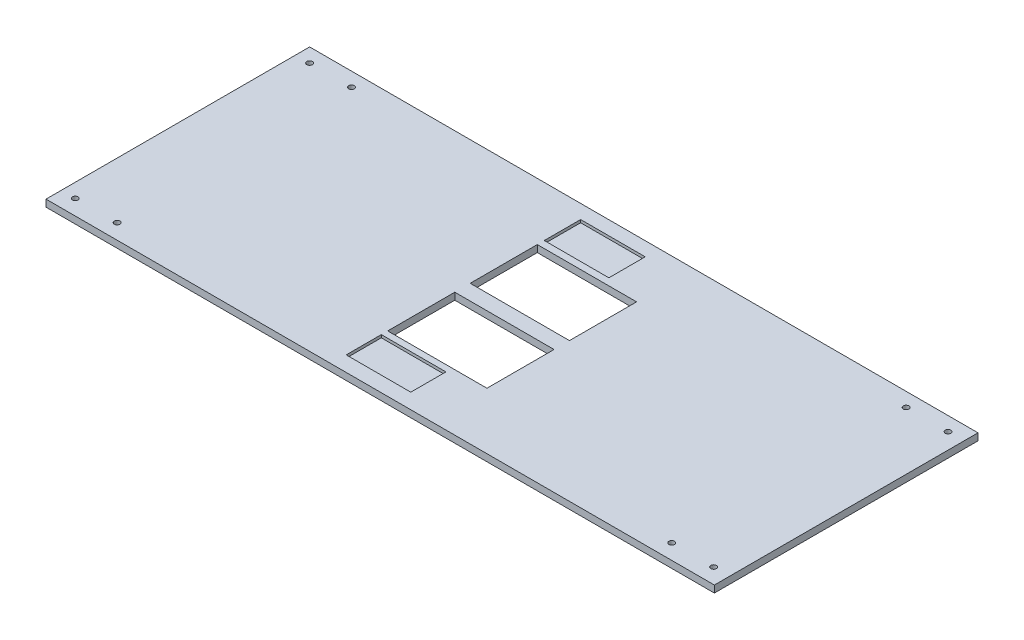
SolidWorks part; units mm, degrees
ref_plane "Plan de face" through (0, 0, 0) normal (0, 0, 1) x (1, 0, 0)
ref_plane "Plan de dessus" through (0, 0, 0) normal (0, 1, 0) x (1, 0, 0)
ref_plane "Plan de droite" through (0, 0, 0) normal (1, 0, 0) x (0, 0, -1)
sketch "Esquisse2" plane through (0, 0, 0) normal (0, 1, 0) x (1, 0, 0)
  line L0 (-85.4449, 137.8619) -> (392.7051, 137.8619)
  line L2 (-85.4449, 137.8619) -> (-85.4449, -50.7281)
  line L3 (-85.4449, -50.7281) -> (392.7051, -50.7281)
  line L4 (392.7051, 137.8619) -> (392.7051, -50.7281)
  line L5 (-85.4449, 137.8619) -> (-75.4449, 137.8619)
  line L6 (-85.4449, -50.7281) -> (-75.4449, -50.7281)
  line L7 (-85.4449, 137.8619) -> (-85.4449, 127.8619)
  line L8 (-85.4449, -50.7281) -> (-85.4449, -39.8416)
  line L9 (392.7051, -50.7281) -> (392.7051, -39.8416)
  line L10 (392.7051, -39.8416) -> (392.7051, 127.8619)
  line L11 (392.7051, 127.8619) -> (381.3005, 127.8619)
  line L12 (-85.4449, -39.8416) -> (381.3005, -39.8416)
  line L13 (392.7051, -39.8416) -> (381.3005, -39.8416)
  line L14 (-75.4449, 137.8619) -> (-75.4449, -50.7281)
  line L15 (381.3005, 127.8619) -> (381.3005, -50.7281)
  line L16 (381.3005, -50.7281) -> (381.3005, 137.8619)
  line L17 (-85.4449, 127.8619) -> (392.7051, 127.8619)
  line L18 (-85.4449, 127.8619) -> (-70.4449, 127.8619)
  line L19 (-70.4449, -39.8416) -> (-70.4449, 127.8619)
  line L20 (392.7051, 127.8619) -> (377.7051, 127.8619)
  line L21 (377.7051, 127.8619) -> (377.7051, -50.7281)
  line L22 (392.7051, -39.8416) -> (377.7051, -39.8416)
  line L23 (381.3005, 127.8619) -> (351.3005, 127.8619)
  line L24 (381.3005, -39.8416) -> (351.3005, -39.8416)
  line L25 (-75.4449, -39.8416) -> (-45.4449, -39.8416)
  line L26 (-75.4449, 127.8619) -> (-45.4449, 127.8619)
  line L27 (-85.4449, 127.8619) -> (118.4351, 127.8619)
  line L28 (118.4351, 127.8619) -> (118.4351, -39.8416)
  line L29 (118.4351, 127.8619) -> (164.6351, 127.8619)
  line L30 (164.6351, 127.8619) -> (164.6351, -39.8416)
  line L31 (164.6351, -39.8416) -> (164.6351, -5.8416)
  line L32 (118.4351, -39.8416) -> (118.4351, -50.7281)
  line L33 (164.6351, 127.8619) -> (164.6351, 93.8619)
  line L34 (118.4351, -50.7281) -> (118.4351, -48.7281)
  line L35 (118.4351, -48.7281) -> (164.6351, -48.7281)
  line L36 (164.6351, -48.7281) -> (164.6351, -50.7281)
  line L37 (164.6351, -50.7281) -> (164.6351, -39.8416)
  line L38 (118.4351, -48.7281) -> (118.4351, -14.7281)
  line L39 (118.4351, -14.7281) -> (164.6351, -14.7281)
  line L40 (164.6351, -14.7281) -> (164.6351, -48.7281)
  line L41 (118.4351, 127.8619) -> (118.4351, 137.8619)
  line L42 (118.4351, 137.8619) -> (118.4351, 135.8619)
  line L43 (118.4351, 135.8619) -> (164.6351, 135.8619)
  line L44 (164.6351, 135.8619) -> (164.6351, 101.8619)
  line L45 (164.6351, 101.8619) -> (118.4351, 101.8619)
  line L46 (118.4351, 101.8619) -> (118.4351, 135.8619)
  line L47 (118.4351, 96.8619) -> (189.4351, 96.8619)
  line L48 (164.6351, 43.5669) -> (164.6351, 53.5669)
  line L49 (118.4351, 96.8619) -> (118.4351, 48.8619)
  line L50 (118.4351, 53.5669) -> (118.4351, 33.5669)
  line L51 (118.4351, 48.8619) -> (164.6351, 48.8619)
  line L52 (118.4351, 101.8619) -> (118.4351, 96.8619)
  line L53 (118.4351, 96.8619) -> (164.6351, 96.8619)
  line L54 (118.4351, -39.8416) -> (118.4351, -35.3126)
  line L55 (118.4351, -14.7281) -> (118.4351, -10.1607)
  line L56 (164.6351, -10.1607) -> (118.4351, -10.1607)
  line L57 (118.4351, -10.1607) -> (118.4351, 37.8393)
  line L58 (118.4351, 37.8393) -> (164.6351, 37.8393)
  line L59 (189.4351, 96.8619) -> (189.4351, 48.8619)
  line L60 (189.4351, 48.8619) -> (118.4351, 48.8619)
  line L61 (118.4351, -10.1607) -> (189.4351, -10.1607)
  line L62 (189.4351, -10.1607) -> (189.4351, 37.8393)
  line L63 (189.4351, 37.8393) -> (118.4351, 37.8393)
  circle A0 centre (-75.4449, 127.8619) radius 2
  circle A1 centre (-75.4449, -39.8416) radius 2
  circle A2 centre (381.3005, 127.8619) radius 2
  circle A3 centre (381.3005, -39.8416) radius 2
  circle A4 centre (351.3005, 127.8619) radius 2
  circle A5 centre (351.3005, -39.8416) radius 2
  circle A6 centre (-45.4449, -39.8416) radius 2
  circle A7 centre (-45.4449, 127.8619) radius 2
extrude "Boss.-Extru.1" add sketch "Esquisse2" along normal blind 5 contours A0 L14 L0 L2 L17 | A1 L14 A0 L17 L2 L12 | A1 L25 L19 L27 A0 L14 | A7 L17 L19 L12 A6 L38 L28 L50 L49 L27 | A1 L12 L2 L3 L14 | A6 L12 L25 A1 L14 L3 L32 | A5 L24 L21 L23 A4 L17 L30 L33 L47 L59 L60 L48 L63 L62 L61 L31 L12 | A4 L23 L17 A2 L16 L0 L41 L43 L44 | A3 L13 L4 L11 A2 L16 | A2 L11 L4 L0 L16 | L28 L58 L30 L48 L51 | L28 L47 L33 L45 | L44 L43 L41 L17 | A7 L27 L41 L0 L14 A0 L17 | L35 L37 L12 L32 | L36 L35 L32 L3 | A5 L12 L37 L36 L3 L21 L24 | L31 L56 L28 L39 | A3 L12 L21 L3 L16 | A3 L16 L3 L4 L13 | A3 L16 A2 L17 L21 L12
sketch "Esquisse3" plane through (0, 0, 0) normal (0, -1, 0) x (1, 0, 0)
  line L1 (118.4351, 14.7281) -> (164.6351, 14.7281)
  line L2 (118.4351, 14.7281) -> (118.4351, 39.8416)
  line L3 (118.4351, 39.8416) -> (164.6351, 39.8416)
  line L4 (164.6351, 14.7281) -> (164.6351, 39.8416)
  line L5 (118.4351, -127.8619) -> (164.6351, -127.8619)
  line L6 (118.4351, -127.8619) -> (118.4351, -101.8619)
  line L7 (118.4351, -101.8619) -> (164.6351, -101.8619)
  line L8 (164.6351, -127.8619) -> (164.6351, -101.8619)
extrude "Boss.-Extru.2" add sketch "Esquisse3" against normal blind 3
